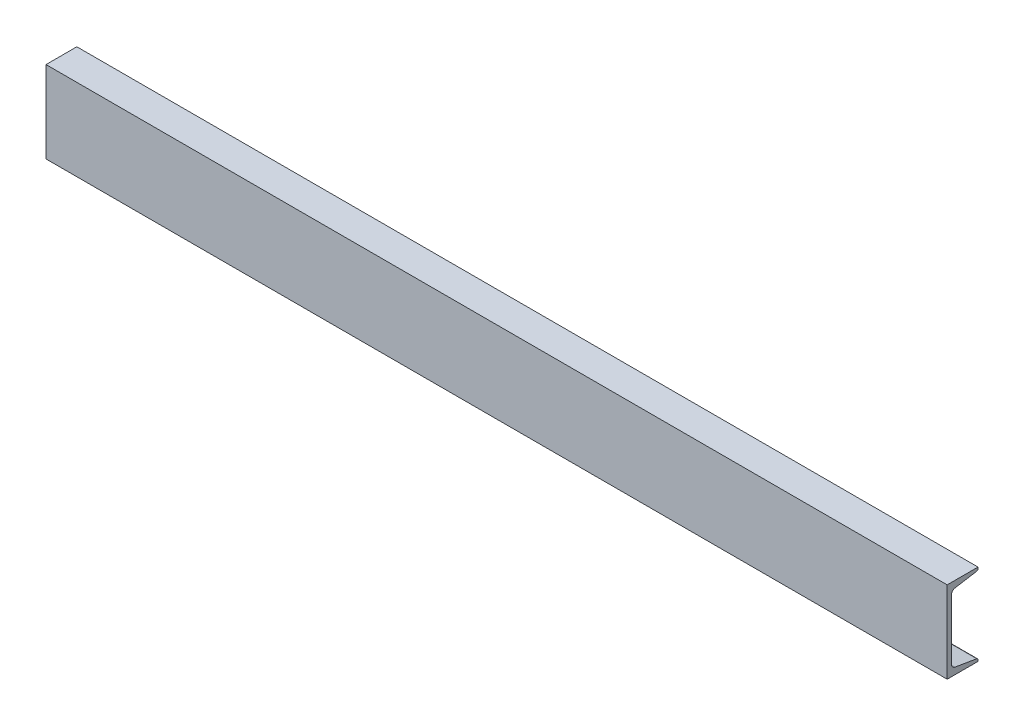
SolidWorks part; units mm, degrees
ref_plane "Alzado" through (0, 0, 0) normal (0, 0, 1) x (1, 0, 0)
ref_plane "Planta" through (0, 0, 0) normal (0, 1, 0) x (1, 0, 0)
ref_plane "Vista lateral" through (0, 0, 0) normal (1, 0, 0) x (0, 0, -1)
sketch "Croquis1" plane through (0, 0, 0) normal (0, 1, 0) x (1, 0, 0)
  line L0 (0, 0) -> (1400, 0)
  dimension "D1" = 1400
other "Canal c 3 X 5(1)"
ref_plane "Plano1" through (0, 0, 0) normal (1, 0, 0) x (0, 0, -1)
sketch "Sketch12" plane through (0, 0, 0) normal (1, 0, 0) x (0, 0, -1)
  line L0 (0, -63.5) -> (0, 63.5)
  line L1 (0, 63.5) -> (47.9, 63.5)
  line L2 (0, -63.5) -> (47.9, -63.5)
  line L5 (31.75, -56.5658) -> (6.35, -56.5658) construction
  line L6 (0, 0) -> (6.5532, 0) construction
  line L12 (6.5532, 46.4895) -> (6.5532, -46.4895)
  line L15 (47.9, 63.5) -> (47.9, 61.3423)
  line L16 (47.9, -63.5) -> (47.9, -61.3423)
  line L17 (12.2837, 53.2542) -> (45.7776, 58.8369)
  line L18 (12.2837, -53.2542) -> (45.7776, -58.8369)
  arc A9 (6.5532, -46.4895) -> (12.2837, -53.2542) centre (13.4112, -46.4895) ccw
  arc A10 (6.5532, 46.4895) -> (12.2837, 53.2542) centre (13.4112, 46.4895) cw
  arc A11 (47.9, 61.3423) -> (45.7776, 58.8369) centre (45.36, 61.3423) cw
  arc A12 (47.9, -61.3423) -> (45.7776, -58.8369) centre (45.36, -61.3423) ccw
  point P4 (47.9, 59.1907)
  point P5 (47.9, -59.1907)
  point P6 (3.2766, 0)
  point P7 (23.95, 63.5)
  point P12 (23.95, -63.5)
  point P13 (0, 0)
  dimension "RI" = 6.858
  dimension "D2" = 9.463
  dimension "RA" = 2.54
  dimension "Depth" = 127
  dimension "BF" = 47.9
  dimension "TW" = 6.5532
  dimension "flange" = 2.1577
  dimension "TF" = 6.9342
